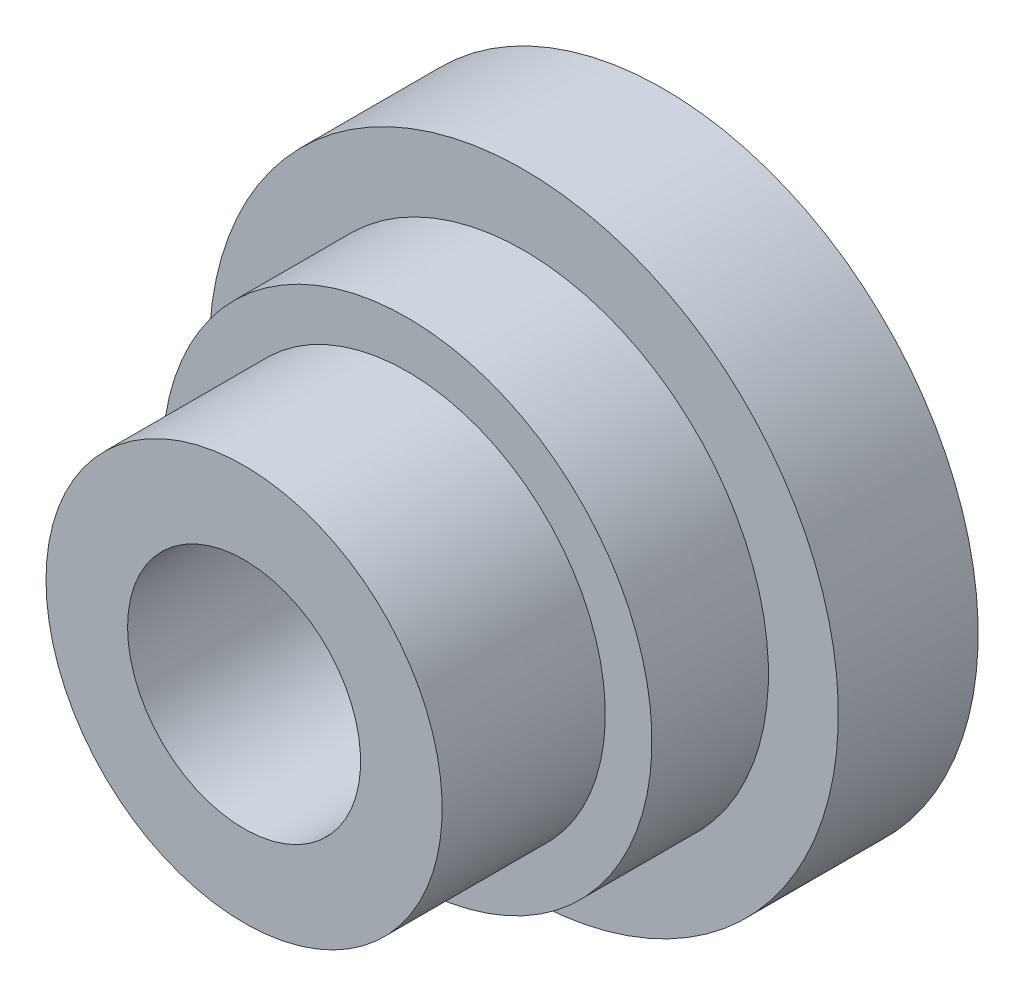
SolidWorks part; units mm, degrees
ref_plane "前基準面" through (0, 0, 0) normal (0, 0, 1) x (1, 0, 0)
ref_plane "上基準面" through (0, 0, 0) normal (0, 1, 0) x (1, 0, 0)
ref_plane "右基準面" through (0, 0, 0) normal (1, 0, 0) x (0, 0, -1)
sketch "草圖1" plane through (0, 0, 0) normal (1, 0, 0) x (0, 0, -1)
  line L0 (0, 0) -> (-46.0408, 0) construction
  line L1 (0, 10) -> (0, 27)
  line L2 (0, 27) -> (-12, 27)
  line L3 (-12, 27) -> (-12, 21)
  line L4 (-12, 21) -> (-22, 21)
  line L5 (-22, 21) -> (-22, 17)
  line L6 (-22, 17) -> (-36, 17)
  line L7 (-36, 17) -> (-36, 10)
  line L8 (-36, 10) -> (0, 10)
  dimension "D1" = 14
  dimension "D2" = 10
  dimension "D3" = 36
  dimension "D4" = 20
  dimension "D5" = 34
  dimension "D6" = 42
  dimension "D7" = 54
revolve "旋轉1" add sketch "草圖1" angle 360 about L0
